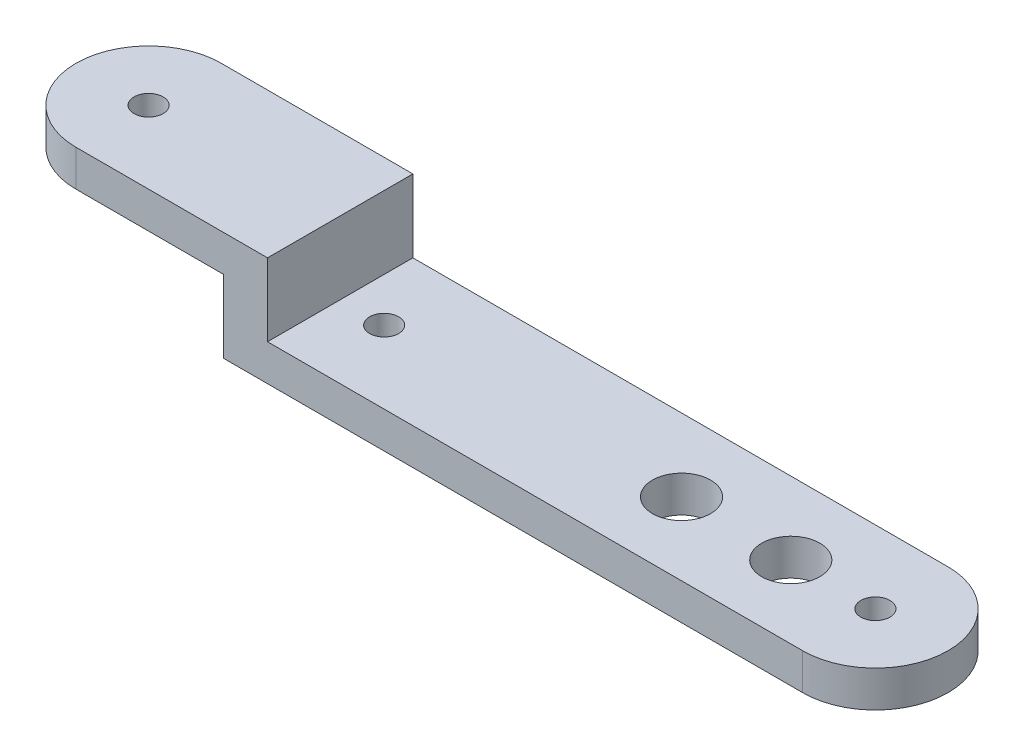
SolidWorks part; units mm, degrees
ref_plane "前视基准面" through (0, 0, 0) normal (0, 0, 1) x (1, 0, 0)
ref_plane "上视基准面" through (0, 0, 0) normal (0, 1, 0) x (1, 0, 0)
ref_plane "右视基准面" through (0, 0, 0) normal (1, 0, 0) x (0, 0, -1)
other "Configuration Table"
sketch "草图2" plane through (0, 0, 0) normal (0, 1, 0) x (1, 0, 0)
  line L0 (0, 0) -> (100, 0) construction
  line L1 (0, 10) -> (100, 10)
  line L2 (0, -10) -> (100, -10)
  arc A0 (0, 10) -> (0, -10) centre (0, 0) ccw
  arc A1 (100, -10) -> (100, 10) centre (100, 0) ccw
  circle A2 centre (0, 0) radius 2
  circle A3 centre (10.1668, 0) radius 2
  circle A4 centre (20.8337, 0) radius 2
  circle A5 centre (32.4122, 0) radius 2
  circle A6 centre (100, 0) radius 2
  circle A7 centre (88.3574, 0) radius 4
  circle A8 centre (73.3214, 0) radius 4
  point P3 (50, 0)
  dimension "D1" = 100
  dimension "D2" = 20
extrude "凸台-拉伸1" add sketch "草图2" along normal blind 15
sketch "草图3" plane through (0, 15, 0) normal (0, 1, 0) x (1, 0, 0)
  line L1 (26.3617, 16.742) -> (124.6448, 16.742)
  line L2 (26.3617, 16.742) -> (26.3617, -26.1973)
  line L3 (26.3617, -26.1973) -> (124.6448, -26.1973)
  line L4 (124.6448, 16.742) -> (124.6448, -26.1973)
extrude "切除-拉伸1" cut sketch "草图3" against normal blind 10
sketch "草图4" plane through (0, 15, 0) normal (0, 1, 0) x (1, 0, 0)
  line L1 (6.2367, 5.3782) -> (23.8461, 5.3782)
  line L2 (6.2367, 5.3782) -> (6.2367, -4.9445)
  line L3 (6.2367, -4.9445) -> (23.8461, -4.9445)
  line L4 (23.8461, 5.3782) -> (23.8461, -4.9445)
extrude "凸台-拉伸2" add sketch "草图4" against normal blind 15
sketch "草图5" plane through (0, 0, 0) normal (0, -1, 0) x (1, 0, 0)
  line L1 (-15.7967, 13.4456) -> (20.3022, 13.4456)
  line L2 (-15.7967, 13.4456) -> (-15.7967, -12.8384)
  line L3 (-15.7967, -12.8384) -> (20.3022, -12.8384)
  line L4 (20.3022, 13.4456) -> (20.3022, -12.8384)
extrude "切除-拉伸2" cut sketch "草图5" against normal blind 10
